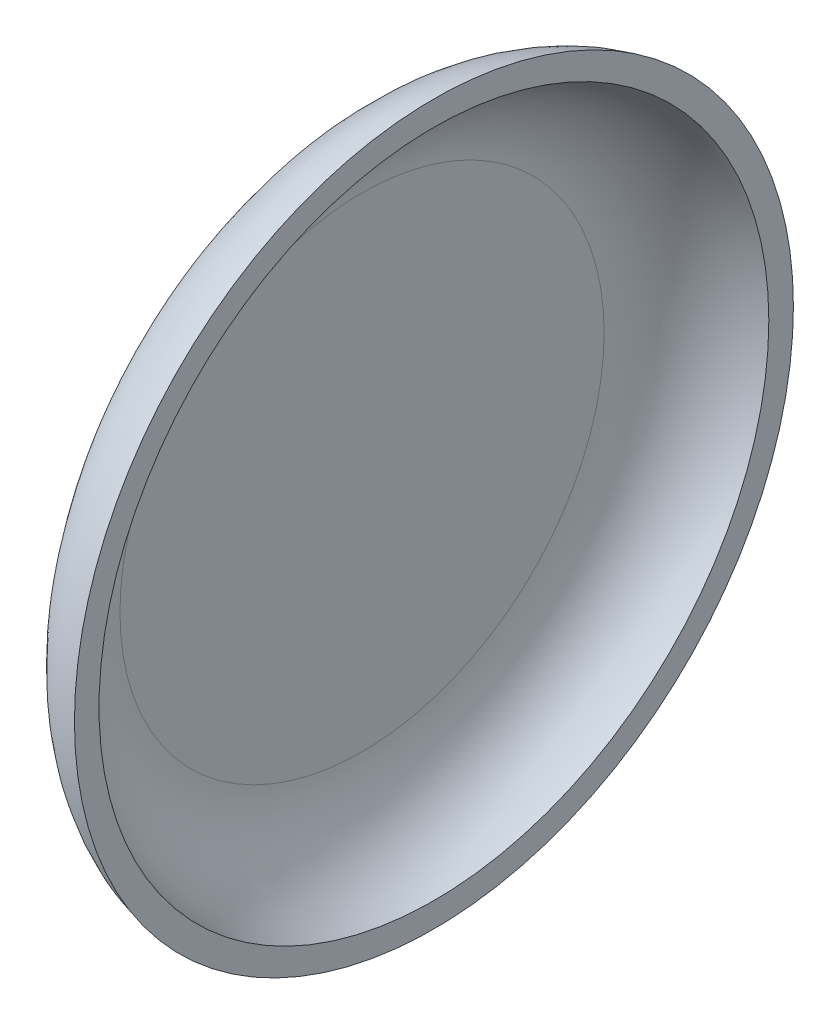
SolidWorks part; units mm, degrees
ref_plane "Front Plane" through (0, 0, 0) normal (0, 0, 1) x (1, 0, 0)
ref_plane "Top Plane" through (0, 0, 0) normal (0, 1, 0) x (1, 0, 0)
ref_plane "Right Plane" through (0, 0, 0) normal (1, 0, 0) x (0, 0, -1)
sketch "Sketch1" plane through (0, 0, 0) normal (0, 0, 1) x (1, 0, 0)
  line L0 (0, 12.5969) -> (0, 0) construction
  line L1 (0, 0) -> (-13.4884, 0) construction
  line L2 (-4, 0) -> (-4, 10.101)
  line L3 (0, 12.5969) -> (0, 15) construction
  line L4 (-3, 0) -> (-3, 10.101)
  line L5 (0, 15) -> (0, 13.974)
  line L6 (-4, 0) -> (-3, 0)
  arc A0 (-4, 10.101) -> (0, 15) centre (1, 10.101) cw
  arc A1 (-3, 10.101) -> (0, 13.974) centre (1, 10.101) cw
  arc A3 (-3, 10.101) -> (0.2, 14.0202) centre (1, 10.101) cw construction
  dimension "D3" = 5
  dimension "D1" = 15
  dimension "D2" = 4
  dimension "D4" = 1
revolve "Revolve1" add sketch "Sketch1" angle 360 about L1
